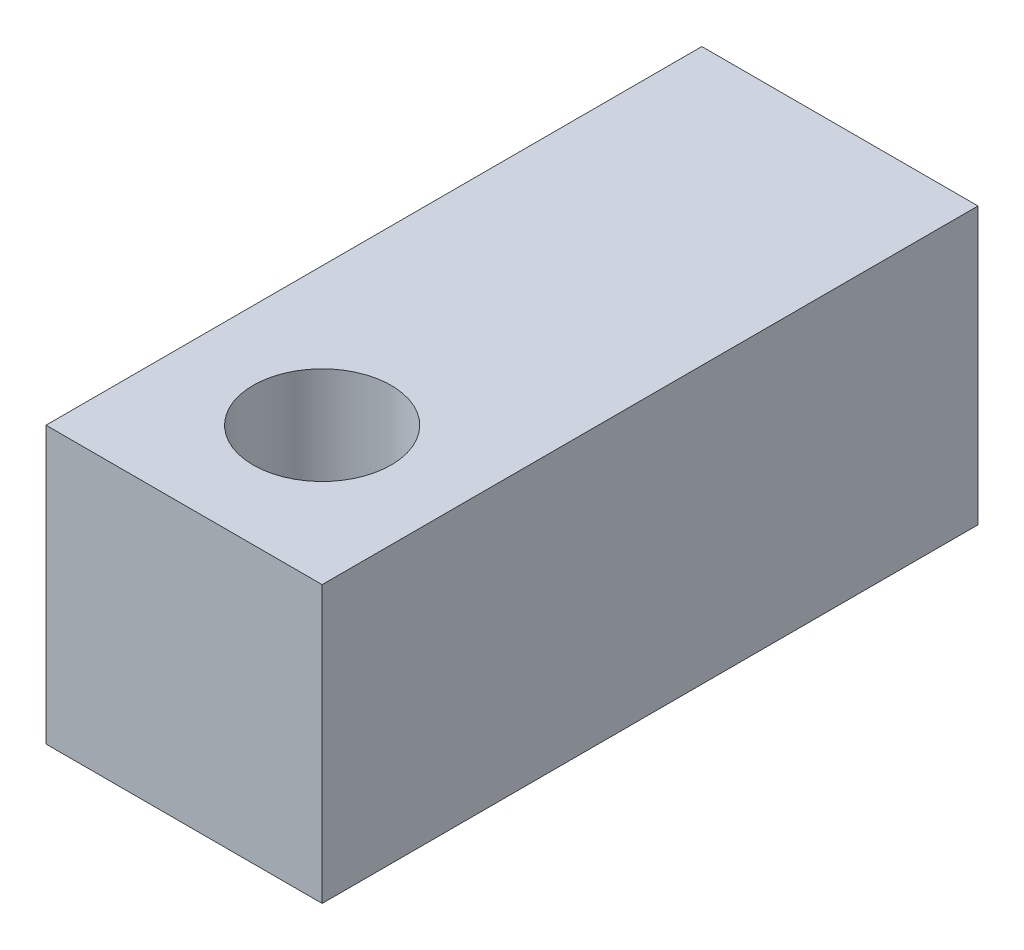
SolidWorks part; units mm, degrees
material "6061-T6 (SS)"
ref_plane "Front Plane" through (0, 0, 0) normal (0, 0, 1) x (1, 0, 0)
ref_plane "Top Plane" through (0, 0, 0) normal (0, 1, 0) x (1, 0, 0)
ref_plane "Right Plane" through (0, 0, 0) normal (1, 0, 0) x (0, 0, -1)
sketch "Sketch1" plane through (0, 0, 0) normal (0, 0, 1) x (1, 0, 0)
  line L1 (-8, -8) -> (8, -8)
  line L2 (-8, -8) -> (-8, 8)
  line L3 (-8, 8) -> (8, 8)
  line L4 (8, -8) -> (8, 8)
extrude "Shaft_Support" add sketch "Sketch1" along normal blind 38
sketch "Sketch2" plane through (0, 0, 0) normal (0, 1, 0) x (1, 0, 0)
  circle A0 centre (0, -30) radius 4
extrude "D8_Guide_Shaft_Seat" cut sketch "Sketch2" against normal through all and the other way through all
sketch "Sketch3" plane through (0, 0, 0) normal (0, 0, -1) x (-1, 0, 0)
  circle A0 centre (0, 0) radius 2.5
extrude "M5_Bottom_Thread_Major_Envelope" cut sketch "Sketch3" against normal blind 8
